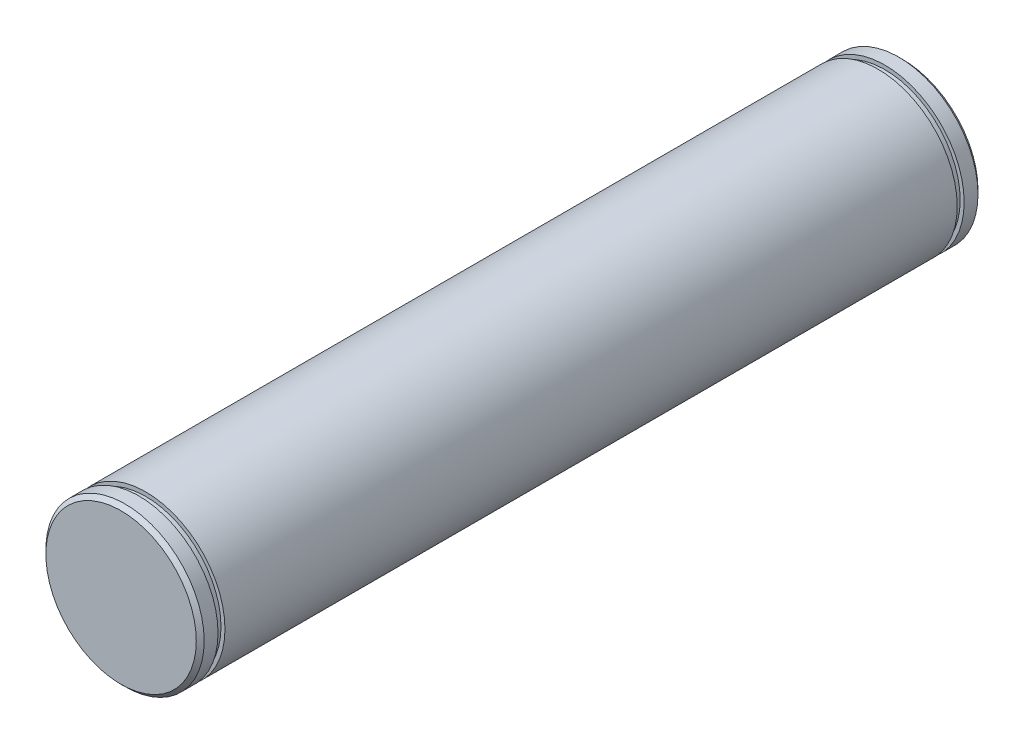
SolidWorks part; units mm, degrees
material "铸造合金钢"
ref_plane "前视基准面" through (0, 0, 0) normal (0, 0, 1) x (1, 0, 0)
ref_plane "上视基准面" through (0, 0, 0) normal (0, 1, 0) x (1, 0, 0)
ref_plane "右视基准面" through (0, 0, 0) normal (1, 0, 0) x (0, 0, -1)
sketch "草图1" plane through (0, 0, 0) normal (0, 0, 1) x (1, 0, 0)
  circle A0 centre (0, 0) radius 4
  dimension "D1" = 8
extrude "凸台-拉伸1" add sketch "草图1" along normal mid plane 39.5
sketch "草图2" plane through (0, 0, 0) normal (1, 0, 0) x (0, 0, -1)
  line L1 (19.75, 4) -> (-19.75, 4) construction
  line L2 (-18.85, 4) -> (-18.5, 4)
  line L3 (-18.85, 4) -> (-18.85, 3.8)
  line L4 (-18.85, 3.8) -> (-18.5, 3.8)
  line L5 (-18.5, 4) -> (-18.5, 3.8)
  line L6 (-18.5, 3.9) -> (18.5, 3.9) construction
  line L7 (18.5, 4) -> (18.85, 4)
  line L8 (18.5, 4) -> (18.5, 3.8)
  line L9 (18.5, 3.8) -> (18.85, 3.8)
  line L10 (18.85, 4) -> (18.85, 3.8)
  line L11 (18.5, 3.9) -> (0, 0) construction
  line L12 (0, 0) -> (0, 3.9) construction
  dimension "D1" = 37
  dimension "D2" = 0.35
  dimension "D3" = 0.2
ref_axis "基准轴1" through (0, 0, 19.75) along (0, 0, -1)
revolve "切除-旋转1" cut sketch "草图2" angle 360 about axis through (0, 0, 19.75) along (0, 0, -1)
chamfer "倒角1" distance 0.2 angle 45 2 edges at (4, 0, -19.75) (4, 0, 19.75)
